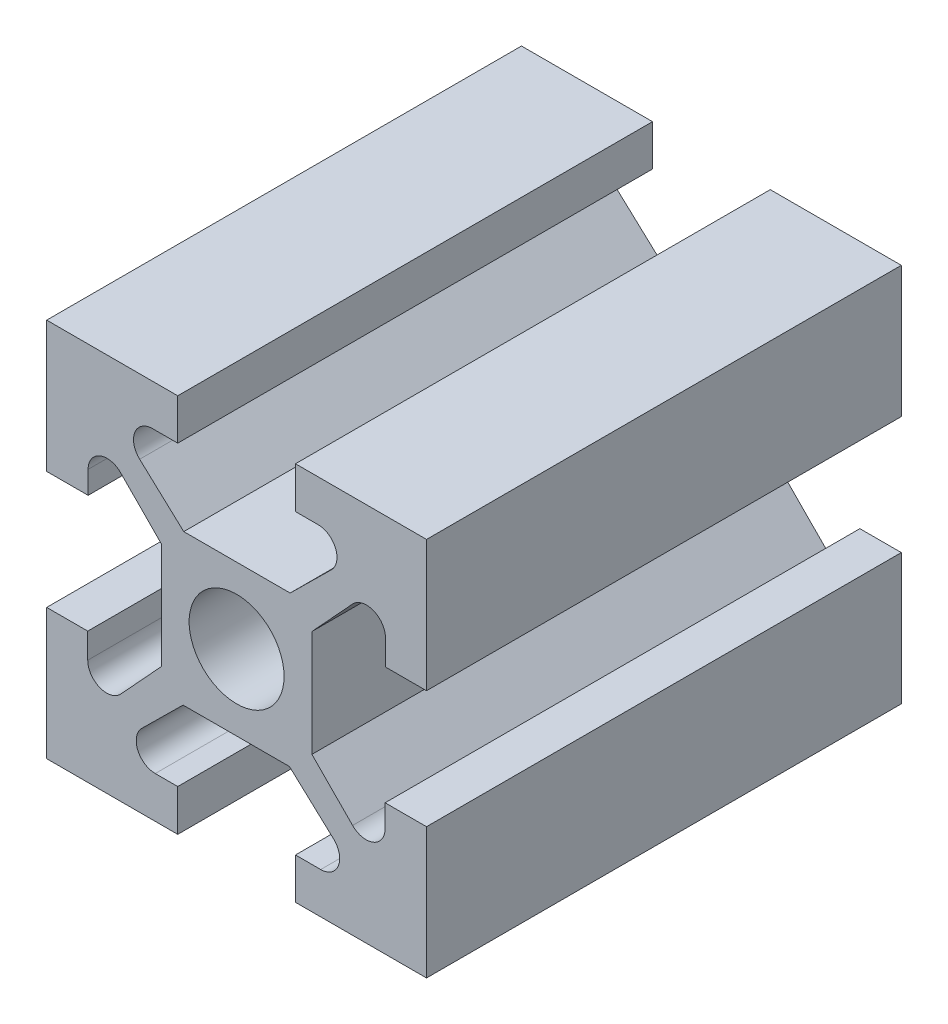
SolidWorks part; units mm, degrees
ref_plane "Front Plane" through (0, 0, 0) normal (0, 0, 1) x (1, 0, 0)
ref_plane "Top Plane" through (0, 0, 0) normal (0, 1, 0) x (1, 0, 0)
ref_plane "Right Plane" through (0, 0, 0) normal (1, 0, 0) x (0, 0, -1)
sketch "Sketch2" plane through (0, 0, 0) normal (0, 0, 1) x (1, 0, 0)
  line L0 (-295.6365, 99.3001) -> (355.6968, 99.3001) construction
  line L1 (53, 177) -> (305, 177) construction
  line L2 (0, 9.9554) -> (0, -10.0446) construction
  line L7 (-10, -10) -> (-3.1, -10)
  line L8 (-10, -10) -> (-10, -3.1)
  line L9 (-10, 10) -> (-3.1, 10)
  line L10 (10, -10) -> (10, -3.1)
  line L11 (-10, -10) -> (10, 10) construction
  line L12 (-10, 10) -> (10, -10) construction
  line L13 (-10, 0) -> (10, 0) construction
  line L14 (-10, 3.1) -> (-7.8186, 3.1)
  line L15 (-7.8186, 3.1) -> (-7.8186, 4.2854)
  line L16 (-6.1072, 4.9882) -> (-3.9647, 2.8197)
  line L17 (-3.9647, 2.8197) -> (-3.9647, 0)
  line L18 (-3.1, 10) -> (-3.1, 7.839)
  line L19 (-3.1, 7.839) -> (-4.4279, 7.839)
  line L20 (-5.1052, 6.1033) -> (-2.7827, 3.9647)
  line L21 (-2.7827, 3.9647) -> (0, 3.9647)
  line L22 (3.1, 10) -> (3.1, 7.8186)
  line L23 (3.1, 7.8186) -> (4.2854, 7.8186)
  line L24 (4.9882, 6.1072) -> (2.8197, 3.9647)
  line L25 (2.8197, 3.9647) -> (0, 3.9647)
  line L26 (6.1033, 5.1052) -> (3.9647, 2.7827)
  line L27 (3.9647, 2.7827) -> (3.9647, 0)
  line L28 (7.839, 3.1) -> (7.839, 4.4279)
  line L29 (10, 3.1) -> (7.839, 3.1)
  line L30 (10, -3.1) -> (7.8186, -3.1)
  line L31 (7.8186, -3.1) -> (7.8186, -4.2854)
  line L32 (6.1072, -4.9882) -> (3.9647, -2.8197)
  line L33 (3.9647, -2.8197) -> (3.9647, 0)
  line L34 (5.1052, -6.1033) -> (2.7827, -3.9647)
  line L35 (2.7827, -3.9647) -> (0, -3.9647)
  line L36 (3.1, -7.839) -> (4.4279, -7.839)
  line L37 (3.1, -10) -> (3.1, -7.839)
  line L38 (-3.1, -10) -> (-3.1, -7.8186)
  line L39 (-3.1, -7.8186) -> (-4.2854, -7.8186)
  line L40 (-4.9882, -6.1072) -> (-2.8197, -3.9647)
  line L41 (-2.8197, -3.9647) -> (0, -3.9647)
  line L42 (-6.1033, -5.1052) -> (-3.9647, -2.7827)
  line L43 (-3.9647, -2.7827) -> (-3.9647, 0)
  line L44 (-7.839, -3.1) -> (-7.839, -4.4279)
  line L45 (-10, -3.1) -> (-7.839, -3.1)
  line L46 (3.1, 10) -> (10, 10)
  line L47 (10, 3.1) -> (10, 10)
  line L48 (3.1, -10) -> (10, -10)
  line L49 (-10, 3.1) -> (-10, 10)
  circle A1 centre (0, 0) radius 2.5
  arc A2 (-4.4279, 7.839) -> (-5.1052, 6.1033) centre (-4.4279, 6.839) ccw
  arc A3 (-7.8186, 4.2854) -> (-6.1072, 4.9882) centre (-6.8186, 4.2854) cw
  arc A4 (4.2854, 7.8186) -> (4.9882, 6.1072) centre (4.2854, 6.8186) cw
  arc A5 (7.839, 4.4279) -> (6.1033, 5.1052) centre (6.839, 4.4279) ccw
  arc A6 (7.8186, -4.2854) -> (6.1072, -4.9882) centre (6.8186, -4.2854) cw
  arc A7 (4.4279, -7.839) -> (5.1052, -6.1033) centre (4.4279, -6.839) ccw
  arc A8 (-4.2854, -7.8186) -> (-4.9882, -6.1072) centre (-4.2854, -6.8186) cw
  arc A9 (-7.839, -4.4279) -> (-6.1033, -5.1052) centre (-6.839, -4.4279) ccw
  dimension "D1" = 3.1
  dimension "D5" = 1
  dimension "D2" = 20
  dimension "D3" = 20
  dimension "D4" = 3.1
  dimension "D6" = 4
extrude "Boss-Extrude1" add sketch "Sketch2" along normal blind 25
